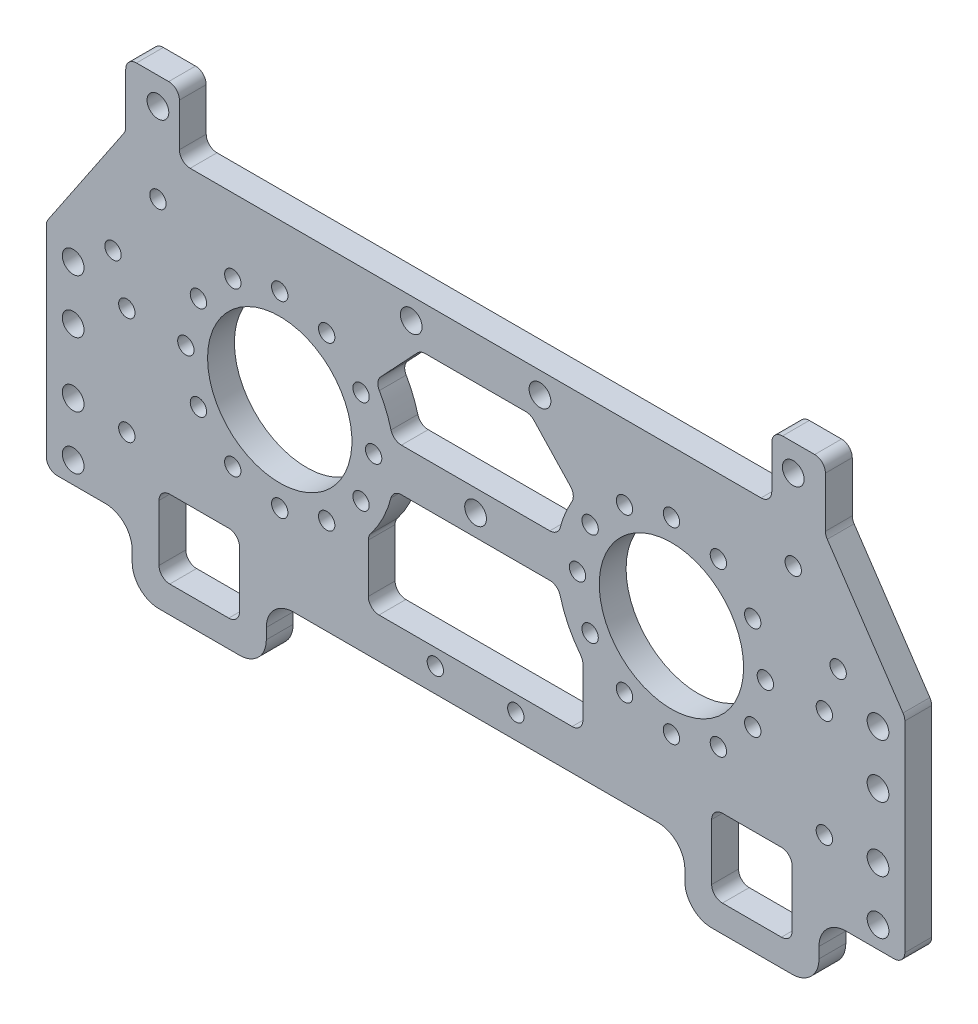
SolidWorks part; units mm, degrees
material "Thornel Mat VMA"
ref_plane "前视基准面" through (0, 0, 0) normal (0, 0, 1) x (1, 0, 0)
ref_plane "上视基准面" through (0, 0, 0) normal (0, 1, 0) x (1, 0, 0)
ref_plane "右视基准面" through (0, 0, 0) normal (1, 0, 0) x (0, 0, -1)
other "Configuration Table"
sketch "草图1" plane through (0, 0, 0) normal (0, 0, 1) x (1, 0, 0)
  line L1 (-80, -30.25) -> (80, -30.25)
  line L2 (-80, -30.25) -> (-80, 30.25)
  line L3 (-80, 30.25) -> (80, 30.25)
  line L4 (80, -30.25) -> (80, 30.25)
  line L5 (-80, -30.25) -> (80, 30.25) construction
  line L6 (-80, 30.25) -> (80, -30.25) construction
  point P0 (0, 0)
  dimension "D1" = 60.5
  dimension "D2" = 160
extrude "凸台-拉伸1" add sketch "草图1" along normal blind 5
sketch "草图2" plane through (0, 0, 5) normal (0, 0, 1) x (1, 0, 0)
  circle A0 centre (36.5, 1.25) radius 30 construction
  circle A2 centre (36.5, 1.25) radius 30 construction
  circle A5 centre (36.5, 1.25) radius 13.45
  circle A6 centre (36.5, 1.25) radius 17.5 construction
  circle A10 centre (36.5, 18.75) radius 1.525
  circle A11 centre (45.25, 16.4054) radius 1.525
  circle A12 centre (51.6554, 10) radius 1.525
  circle A13 centre (54, 1.25) radius 1.525
  circle A14 centre (51.6554, -7.5) radius 1.525
  circle A15 centre (45.25, -13.9054) radius 1.525
  circle A16 centre (36.5, -16.25) radius 1.525
  circle A17 centre (27.75, -13.9054) radius 1.525
  circle A18 centre (21.3446, -7.5) radius 1.525
  circle A19 centre (19, 1.25) radius 1.525
  circle A20 centre (21.3446, 10) radius 1.525
  circle A21 centre (27.75, 16.4054) radius 1.525
  point P37 (36.5, 1.25)
  dimension "D1" = 26.9
  dimension "D2" = 35
  dimension "D3" = 3.05
  dimension "D4" = 12
extrude "切除-拉伸1" cut sketch "草图2" against normal blind 34
mirror "镜向1" about plane through (0, 0, 0) normal (1, 0, 0) of "切除-拉伸1"
sketch "草图3" plane through (0, 0, 5) normal (0, 0, 1) x (1, 0, 0)
  circle A0 centre (0, 1.25) radius 1.65 construction
  circle A1 centre (12, 26.25) radius 1.65 construction
  circle A2 centre (-12, 26.25) radius 1.65 construction
  circle A3 centre (0, 1.25) radius 1.65 construction
  circle A4 centre (12, 26.25) radius 1.65 construction
  circle A5 centre (-12, 26.25) radius 1.65 construction
  circle A6 centre (-12, 26.25) radius 2.025
  circle A7 centre (0, 1.25) radius 2.025
  circle A8 centre (12, 26.25) radius 2.025
  dimension "D1" = 4.05
extrude "切除-拉伸2" cut sketch "草图3" against normal blind 10
sketch "草图4" plane through (0, 0, 5) normal (0, 0, 1) x (1, 0, 0)
  circle A0 centre (7.5, -27.25) radius 1.25 construction
  circle A1 centre (-7.5, -27.25) radius 1.25 construction
  circle A2 centre (7.5, -27.25) radius 1.25 construction
  circle A3 centre (-7.5, -27.25) radius 1.25 construction
  circle A4 centre (7.5, -27.25) radius 1.525
  circle A5 centre (-7.5, -27.25) radius 1.525
  dimension "D1" = 3.05
extrude "切除-拉伸3" cut sketch "草图4" against normal blind 10
sketch "草图5" plane through (0, 0, 5) normal (0, 0, 1) x (1, 0, 0)
  line L0 (80, -30.25) -> (80, 30.25) construction
  line L2 (-80, -30.25) -> (80, -30.25)
  line L7 (-80, -30.25) -> (-80, -31.75)
  line L8 (-80, -31.75) -> (80, -31.75)
  line L9 (80, -30.25) -> (80, -31.75)
  dimension "D1" = 1.5
extrude "凸台-拉伸2" add sketch "草图5" against normal up to surface (5 mm away) up to face at (5.975, -27.25, 0)
sketch "草图6" plane through (0, 0, 5) normal (0, 0, 1) x (1, 0, 0)
  line L0 (80, -31.75) -> (80, 30.25) construction
  line L1 (-80, -31.75) -> (80, -31.75) construction
  line L3 (39, -43.75) -> (64, -43.75)
  line L4 (39, -43.75) -> (39, -19.75)
  line L5 (39, -19.75) -> (64, -19.75)
  line L6 (64, -43.75) -> (64, -19.75)
  line L7 (39, -43.75) -> (64, -19.75) construction
  line L8 (39, -19.75) -> (64, -43.75) construction
  point P9 (51.5, -31.75)
  dimension "D1" = 12
  dimension "D2" = 25
  dimension "D3" = 16
extrude "凸台-拉伸3" add sketch "草图6" against normal up to surface (5 mm away) up to face at (5.975, -27.25, 0)
mirror "镜向2" about plane through (0, 0, 0) normal (1, 0, 0) of "凸台-拉伸3"
fillet "圆角1" radius 5 8 edges at (-64, -31.75, 2.5) (-64, -43.75, 2.5) (-39, -43.75, 2.5) (-39, -31.75, 2.5) (64, -31.75, 2.5) (64, -43.75, 2.5) (39, -43.75, 2.5) (39, -31.75, 2.5)
sketch "草图7" plane through (0, 0, 5) normal (0, 0, 1) x (1, 0, 0)
  line L0 (44, -43.75) -> (59, -43.75) construction
  line L1 (44, -38.75) -> (59, -38.75)
  line L2 (44, -38.75) -> (44, -24.25)
  line L3 (44, -24.25) -> (59, -24.25)
  line L4 (59, -38.75) -> (59, -24.25)
  line L5 (44, -38.75) -> (59, -24.25) construction
  line L6 (44, -24.25) -> (59, -38.75) construction
  circle A2 centre (36.5, -16.25) radius 1.525 construction
  point P0 (51.5, -31.5)
  dimension "D1" = 5
  dimension "D2" = 5
  dimension "D3" = 5
  dimension "D4" = 8
extrude "切除-拉伸4" cut sketch "草图7" against normal up to surface (5 mm away) up to face at (0, -30.35, 0)
mirror "镜向3" about plane through (0, 0, 0) normal (1, 0, 0) of "切除-拉伸4"
fillet "圆角2" radius 2 8 edges at (-44, -38.75, 2.5) (-59, -38.75, 2.5) (59, -24.25, 2.5) (59, -38.75, 2.5) (44, -38.75, 2.5) (44, -24.25, 2.5) (-44, -24.25, 2.5) (-59, -24.25, 2.5)
sketch "草图8" plane through (0, 0, 0) normal (0, 0, -1) x (-1, 0, 0)
  line L1 (-55.2, 42.25) -> (-55.2, 30.25)
  line L2 (-80, 30.25) -> (80, 30.25) construction
  line L3 (-55.2, 42.25) -> (-65.2, 42.25)
  line L4 (-65.2, 42.25) -> (-65.2, 30.25)
  line L5 (-65.2, 30.25) -> (-55.2, 30.25)
  dimension "D1" = 10
  dimension "D2" = 55.2
  dimension "D3" = 12
extrude "凸台-拉伸4" add sketch "草图8" against normal up to surface (5 mm away) up to face at (9.025, -27.25, 5)
mirror "镜向4" about plane through (0, 0, 0) normal (1, 0, 0) of "凸台-拉伸4"
sketch "草图11" plane through (0, 0, 0) normal (0, 0, -1) x (-1, 0, 0)
  line L0 (-80, 8.25) -> (-70, 8.25) construction
  line L1 (-80, 8.25) -> (-70, 8.25) construction
  line L2 (-65.2, 30.25) -> (-80, 8.25)
  line L3 (-80, 8.25) -> (-80, 30.25)
  line L4 (-80, 30.25) -> (-65.2, 30.25)
  line L5 (0, 0) -> (0, 36.978) construction
  line L6 (80, 30.25) -> (65.2, 30.25)
  line L7 (80, 8.25) -> (80, 30.25)
  line L8 (65.2, 30.25) -> (80, 8.25)
extrude "切除-拉伸5" cut sketch "草图11" against normal up to surface (5 mm away) up to face at (9.025, -27.25, 5)
sketch "草图12" plane through (0, 0, 0) normal (0, 0, -1) x (-1, 0, 0)
  line L0 (0, 0) -> (0, 37.775) construction
  circle A0 centre (75, 4.25) radius 1.65 construction
  circle A1 centre (75, -27.75) radius 1.65 construction
  circle A2 centre (75, 4.25) radius 1.65 construction
  circle A3 centre (75, -27.75) radius 1.65 construction
  circle A4 centre (75, 4.25) radius 2.025
  circle A5 centre (75, -27.75) radius 2.025
  circle A6 centre (-75, -27.75) radius 1.65 construction
  circle A7 centre (-75, 4.25) radius 1.65 construction
  circle A8 centre (-75, -27.75) radius 2.025
  circle A9 centre (-75, 4.25) radius 2.025
  dimension "D1" = 4.05
extrude "切除-拉伸6" cut sketch "草图12" against normal blind 10
sketch "草图13" plane through (0, 0, 0) normal (0, 0, -1) x (-1, 0, 0)
  line L0 (-12, 26.25) -> (12, 26.25) construction
  line L1 (-10.2691, 22.25) -> (-18.7207, 13.25)
  line L2 (-15.4263, 5.25) -> (15.4263, 5.25)
  line L3 (-10.2691, 22.25) -> (10.2691, 22.25)
  line L4 (0, 22.25) -> (0, 0) construction
  line L5 (10.2691, 22.25) -> (18.7207, 13.25)
  arc A0 (-15.4263, 5.25) -> (-18.7207, 13.25) centre (-36.5, 1.25) ccw
  circle A1 centre (-36.5, 1.25) radius 13.45 construction
  circle A2 centre (0, 1.25) radius 2.025 construction
  circle A3 centre (-12, 26.25) radius 2.025 construction
  arc A4 (15.4263, 5.25) -> (18.7207, 13.25) centre (36.5, 1.25) cw
  point P23 (0, 5.25)
  dimension "D1" = 8
  dimension "D2" = 4
  dimension "D3" = 4
  dimension "D4" = 8
  dimension "D5" = 8
extrude "切除-拉伸7" cut sketch "草图13" against normal blind 10
sketch "草图14" plane through (0, 0, 0) normal (0, 0, -1) x (-1, 0, 0)
  line L0 (-15.4263, -2.75) -> (15.4263, -2.75)
  line L1 (-20, -12.4559) -> (-20, -24.25)
  line L2 (-20, -24.25) -> (20, -24.25)
  line L3 (0, 0) -> (0, -24.25) construction
  line L4 (20, -12.4559) -> (20, -24.25)
  arc A0 (-20, -12.4559) -> (-15.4263, -2.75) centre (-36.5, 1.25) ccw
  circle A1 centre (-7.5, -27.25) radius 1.525 construction
  circle A2 centre (0, 1.25) radius 2.025 construction
  arc A3 (20, -12.4559) -> (15.4263, -2.75) centre (36.5, 1.25) cw
  point P18 (0, -2.75)
  dimension "D1" = 42.9
  dimension "D2" = 3
  dimension "D3" = 20
  dimension "D4" = 4
extrude "切除-拉伸8" cut sketch "草图14" against normal blind 10
fillet "圆角3" radius 2 12 edges at (-18.7207, 13.25, 2.5) (-15.4263, 5.25, 2.5) (15.4263, 5.25, 2.5) (18.7207, 13.25, 2.5) (10.2691, 22.25, 2.5) (-10.2691, 22.25, 2.5) (-15.4263, -2.75, 2.5) (-20, -12.4559, 2.5) (-20, -24.25, 2.5) (15.4263, -2.75, 2.5) (20, -12.4559, 2.5) (20, -24.25, 2.5)
fillet "圆角4" radius 2 12 edges at (80, -31.75, 2.5) (-80, -31.75, 2.5) (-80, 8.25, 2.5) (-65.2, 30.25, 2.5) (-65.2, 42.25, 2.5) (-55.2, 42.25, 2.5) (-55.2, 30.25, 2.5) (65.2, 42.25, 2.5) (65.2, 30.25, 2.5) (80, 8.25, 2.5) (55.2, 42.25, 2.5) (55.2, 30.25, 2.5)
sketch "草图15" plane through (0, 0, 5) normal (0, 0, 1) x (1, 0, 0)
  line L0 (0, 30.25) -> (0, -44.825) construction
  line L1 (53.2, 30.25) -> (-53.2, 30.25) construction
  circle A0 centre (-65, 1.75) radius 1.525 construction
  circle A1 centre (-65, -18.25) radius 1.525 construction
  circle A2 centre (-65, 1.75) radius 1.525
  circle A3 centre (-65, -18.25) radius 1.525
  circle A4 centre (65, -18.25) radius 1.525
  circle A5 centre (65, 1.75) radius 1.525
extrude "切除-拉伸9" cut sketch "草图15" against normal blind 10
sketch "草图16" plane through (0, 0, 0) normal (0, 0, -1) x (-1, 0, 0)
  line L0 (-55.2, 32.25) -> (-55.2, 40.25) construction
  line L1 (-57.2, 42.25) -> (-63.2, 42.25) construction
  circle A0 centre (-59.2, 37.25) radius 4 construction
  circle A1 centre (-59.2, 37.25) radius 2.025
  dimension "D1" = 8
  dimension "D3" = 4.05
  dimension "D2" = 5
extrude "切除-拉伸10" cut sketch "草图16" against normal blind 10
mirror "镜向5" about plane through (0, 0, 0) normal (1, 0, 0) of "切除-拉伸10"
sketch "草图17" plane through (0, 0, 0) normal (0, 0, -1) x (-1, 0, 0)
  line L0 (-59.2, 37.25) -> (-59.2, 22.25) construction
  line L1 (-59.2, 22.25) -> (-67.5727, 9.8042) construction
  line L2 (-79.6594, 8.7562) -> (-65.5406, 29.7438) construction
  line L3 (-59.2, 22.25) -> (-44.2, 22.25) construction
  circle A0 centre (-59.2, 22.25) radius 1.525
  circle A1 centre (-67.5727, 9.8042) radius 1.525
  dimension "D3" = 3.05
  dimension "D1" = 15
  dimension "D2" = 15
extrude "切除-拉伸11" cut sketch "草图17" against normal blind 10
mirror "镜向6" about plane through (0, 0, 0) normal (1, 0, 0) of "切除-拉伸11"
sketch "草图19" plane through (0, 0, 0) normal (0, 0, -1) x (-1, 0, 0)
  line L0 (-75, 4.25) -> (-75, -27.75) construction
  line L1 (-75, -11.75) -> (-66.0406, -11.75) construction
  line L2 (0, 0) -> (0, -39.9615) construction
  line L3 (75, -11.75) -> (66.0406, -11.75) construction
  line L4 (75, 4.25) -> (75, -27.75) construction
  circle A0 centre (-75, -5.75) radius 2.025
  circle A1 centre (-75, -17.75) radius 2.025
  circle A2 centre (75, -17.75) radius 2.025
  circle A3 centre (75, -5.75) radius 2.025
  dimension "D1" = 4.05
  dimension "D2" = 12
extrude "切除-拉伸12" cut sketch "草图19" against normal blind 10
